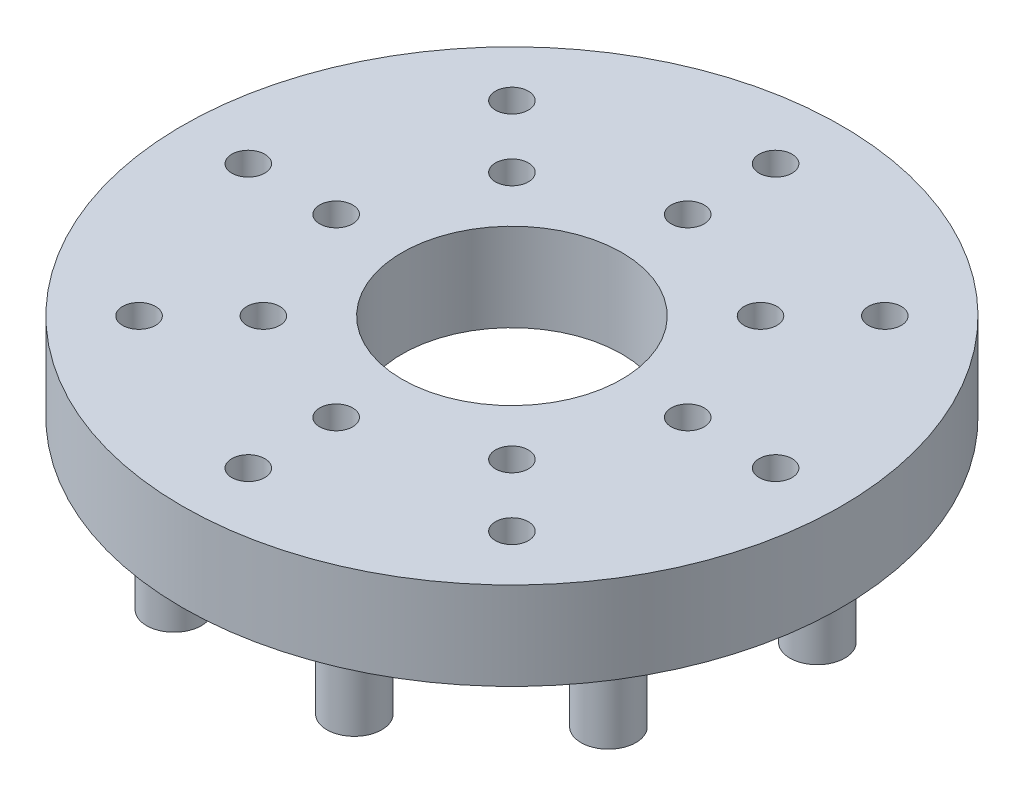
SolidWorks part; units mm, degrees
ref_plane "Front Plane" through (0, 0, 0) normal (0, 0, 1) x (1, 0, 0)
ref_plane "Top Plane" through (0, 0, 0) normal (0, 1, 0) x (1, 0, 0)
ref_plane "Right Plane" through (0, 0, 0) normal (1, 0, 0) x (0, 0, -1)
sketch "Sketch1" plane through (0, 0, 0) normal (0, 1, 0) x (1, 0, 0)
  circle A0 centre (0, 0) radius 190.5
  dimension "D1" = 381
extrude "Boss-Extrude1" add sketch "Sketch1" along normal blind 50.8
sketch "Sketch2" plane through (0, 50.8, 0) normal (0, 1, 0) x (1, 0, 0)
  circle A0 centre (0, 0) radius 63.5
  dimension "D1" = 127
extrude "Cut-Extrude1" cut sketch "Sketch2" against normal through all
sketch "Sketch3" plane through (0, 50.8, 0) normal (0, 1, 0) x (1, 0, 0)
  circle A0 centre (0, 0) radius 101.6 construction
  circle A1 centre (0, 0) radius 152.4 construction
  circle A2 centre (0, 101.6) radius 9.525
  circle A3 centre (71.842, 71.842) radius 9.525
  circle A4 centre (101.6, 0) radius 9.525
  circle A5 centre (71.842, -71.842) radius 9.525
  circle A6 centre (0, -101.6) radius 9.525
  circle A7 centre (-71.842, -71.842) radius 9.525
  circle A8 centre (-101.6, 0) radius 9.525
  circle A9 centre (-71.842, 71.842) radius 9.525
  circle A10 centre (0, 152.4) radius 9.525
  circle A11 centre (107.7631, 107.7631) radius 9.525
  circle A12 centre (152.4, 0) radius 9.525
  circle A13 centre (107.7631, -107.7631) radius 9.525
  circle A14 centre (0, -152.4) radius 9.525
  circle A15 centre (-107.7631, -107.7631) radius 9.525
  circle A16 centre (-152.4, 0) radius 9.525
  circle A17 centre (-107.7631, 107.7631) radius 9.525
  point P23 (0, 0)
  point P39 (0, 0)
  dimension "D1" = 203.2
  dimension "D2" = 304.8
  dimension "D3" = 19.05
  dimension "D4" = 19.05
extrude "Cut-Extrude2" cut sketch "Sketch3" against normal blind 42.926
sketch "Sketch4" plane through (0, 0, 0) normal (0, -1, 0) x (1, 0, 0)
  circle A0 centre (0, 0) radius 152.4 construction
  circle A1 centre (0, -152.4) radius 15.875
  circle A2 centre (-97.9608, -116.7452) radius 15.875
  circle A3 centre (-150.0847, -26.464) radius 15.875
  circle A4 centre (-131.9823, 76.2) radius 15.875
  circle A5 centre (-52.1239, 143.2092) radius 15.875
  circle A6 centre (52.1239, 143.2092) radius 15.875
  circle A7 centre (131.9823, 76.2) radius 15.875
  circle A8 centre (150.0847, -26.464) radius 15.875
  circle A9 centre (97.9608, -116.7452) radius 15.875
  point P24 (0, 0)
  dimension "D1" = 304.8
  dimension "D2" = 31.75
extrude "Boss-Extrude2" add sketch "Sketch4" along normal blind 50.8
